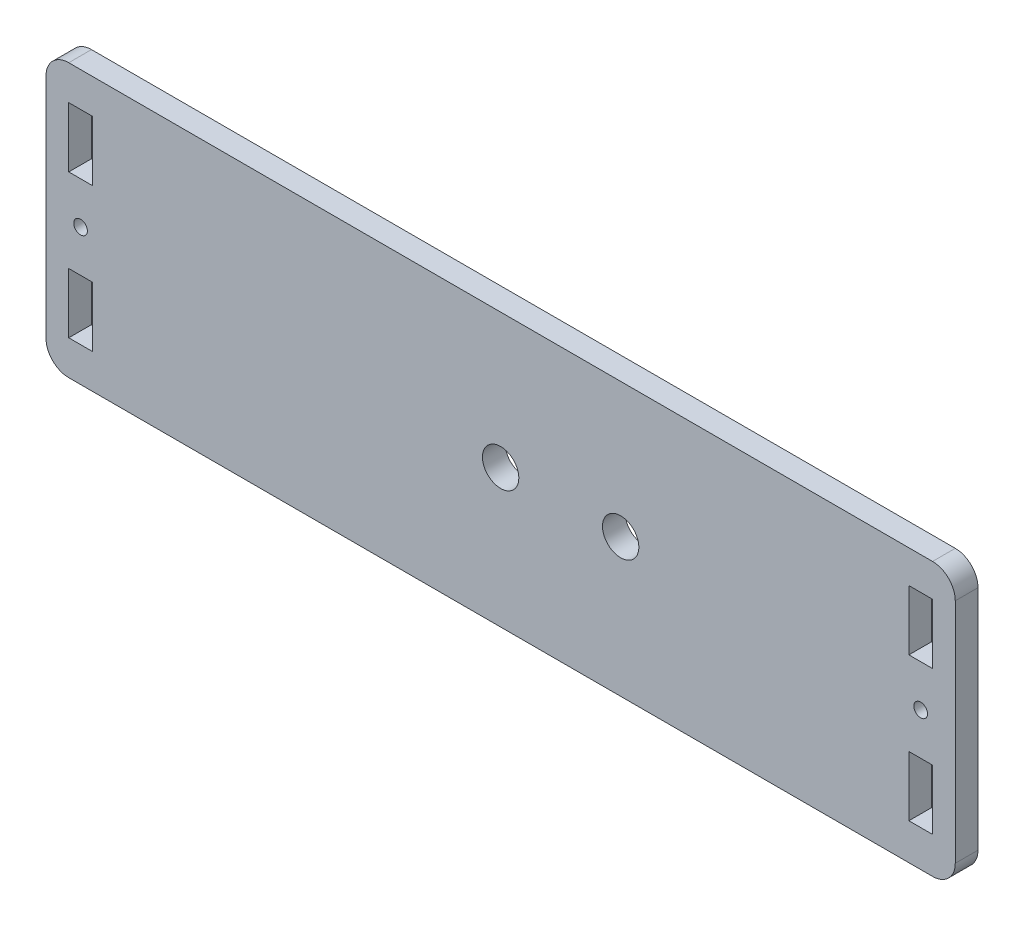
SolidWorks part; units mm, degrees
ref_plane "Front" through (0, 0, 0) normal (0, 0, 1) x (1, 0, 0)
ref_plane "Top" through (0, 0, 0) normal (0, 1, 0) x (1, 0, 0)
ref_plane "Right" through (0, 0, 0) normal (1, 0, 0) x (0, 0, -1)
sketch "Sketch1" plane through (0, 0, 0) normal (0, 0, 1) x (1, 0, 0)
  line L43 (-139.373, 139.351) -> (50.627, 139.351)
  line L44 (-136.77, 100.151) -> (-136.77, 118.551) construction
  line L45 (-144.373, 134.351) -> (-144.373, 84.351)
  line L46 (-134.17, 118.551) -> (-134.17, 131.751)
  line L47 (55.627, 134.351) -> (55.627, 84.351)
  line L48 (50.624, 87.351) -> (45.424, 87.351)
  line L49 (45.424, 87.351) -> (45.424, 100.551)
  line L50 (45.424, 118.951) -> (45.424, 132.151)
  line L51 (50.624, 132.151) -> (50.624, 118.951)
  line L52 (50.624, 100.551) -> (45.424, 100.551)
  line L53 (-139.373, 79.351) -> (50.627, 79.351)
  line L54 (50.624, 100.551) -> (50.624, 87.351)
  line L55 (-51.873, 120.001) -> (-10.473, 120.001) construction
  line L56 (-51.873, 120.001) -> (-51.873, 99.501) construction
  line L57 (-51.873, 99.501) -> (-10.473, 99.501) construction
  line L58 (-10.473, 120.001) -> (-10.473, 99.501) construction
  line L59 (-10.473, 109.751) -> (-17.973, 109.751) construction
  line L60 (-44.373, 139.351) -> (-44.373, 79.351) construction
  line L61 (-51.873, 109.751) -> (-44.373, 109.751) construction
  line L62 (50.624, 132.151) -> (45.424, 132.151)
  line L63 (50.624, 118.951) -> (45.424, 118.951)
  line L64 (48.024, 109.751) -> (55.627, 109.751) construction
  line L65 (48.024, 100.551) -> (48.024, 118.951) construction
  line L66 (-136.77, 109.351) -> (-144.373, 109.351) construction
  line L67 (-139.37, 118.551) -> (-134.17, 118.551)
  line L68 (-139.37, 131.751) -> (-134.17, 131.751)
  line L69 (-139.37, 100.151) -> (-139.37, 86.951)
  line L70 (-139.37, 100.151) -> (-134.17, 100.151)
  line L71 (-139.37, 131.751) -> (-139.37, 118.551)
  line L72 (-134.17, 86.951) -> (-134.17, 100.151)
  line L73 (-139.37, 86.951) -> (-134.17, 86.951)
  circle A6 centre (-55.973, 114.9508) radius 1.6 construction
  circle A7 centre (-55.973, 104.5508) radius 1.6 construction
  circle A8 centre (-6.373, 104.5508) radius 1.6 construction
  circle A9 centre (-6.373, 114.9508) radius 1.6 construction
  arc A10 (50.627, 139.351) -> (55.627, 134.351) centre (50.627, 134.351) cw
  circle A11 centre (48.024, 109.751) radius 1.5
  circle A12 centre (-136.77, 109.351) radius 1.5
  arc A13 (50.627, 79.351) -> (55.627, 84.351) centre (50.627, 84.351) ccw
  arc A14 (-144.373, 84.351) -> (-139.373, 79.351) centre (-139.373, 84.351) ccw
  arc A15 (-139.373, 139.351) -> (-144.373, 134.351) centre (-139.373, 134.351) ccw
  circle A16 centre (-44.373, 109.751) radius 4
  circle A17 centre (-17.973, 109.751) radius 4
  dimension "D1" = 5
extrude "Boss-Extrude1" add sketch "Sketch1" along normal blind 5
